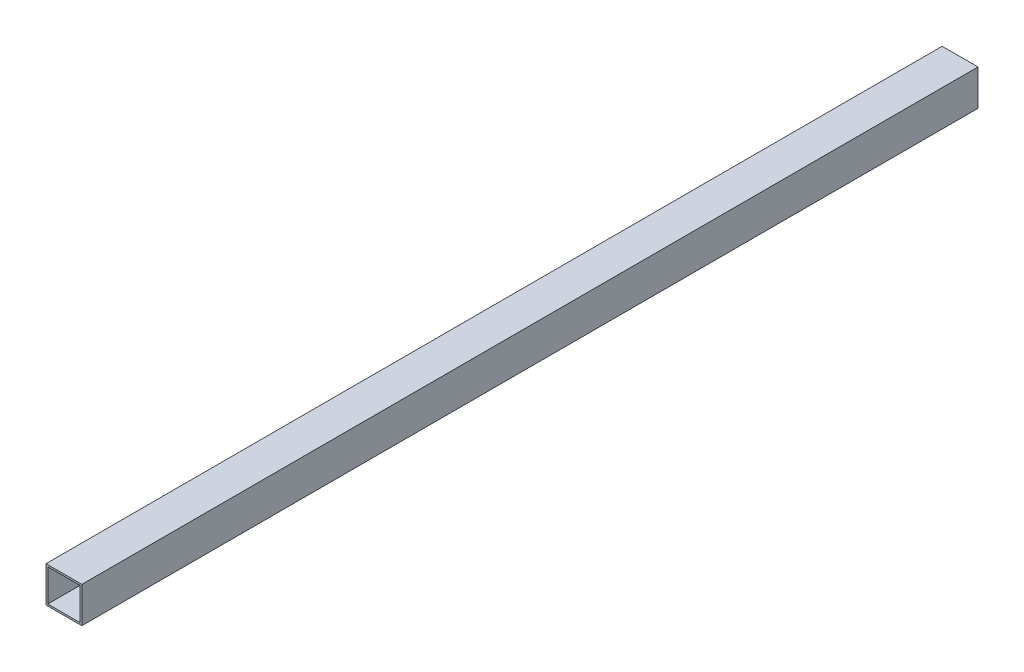
SolidWorks part; units mm, degrees
material "Aleación 1060"
ref_plane "Alzado" through (0, 0, 0) normal (0, 0, 1) x (1, 0, 0)
ref_plane "Planta" through (0, 0, 0) normal (0, 1, 0) x (1, 0, 0)
ref_plane "Vista lateral" through (0, 0, 0) normal (1, 0, 0) x (0, 0, -1)
sketch "Croquis1" plane through (0, 0, 0) normal (0, 0, 1) x (1, 0, 0)
  line L1 (20, -20) -> (-20, -20)
  line L2 (20, -20) -> (20, 20)
  line L3 (20, 20) -> (-20, 20)
  line L4 (-20, -20) -> (-20, 20)
  line L5 (20, -20) -> (-20, 20) construction
  line L6 (20, 20) -> (-20, -20) construction
  point P0 (0, 0)
  dimension "D1" = 40
  dimension "D2" = 40
extrude "Extruir-Lámina1" add sketch "Croquis1" along normal blind 1000 thin
sketch "Croquis2" plane through (0, 20, 0) normal (0, 1, 0) x (1, 0, 0)
  line L0 (0, 0) -> (0, -897.3476) construction
  line L1 (20, 0) -> (-20, 0) construction
  circle A0 centre (0, -190) radius 10 construction
  dimension "D1" = 190
